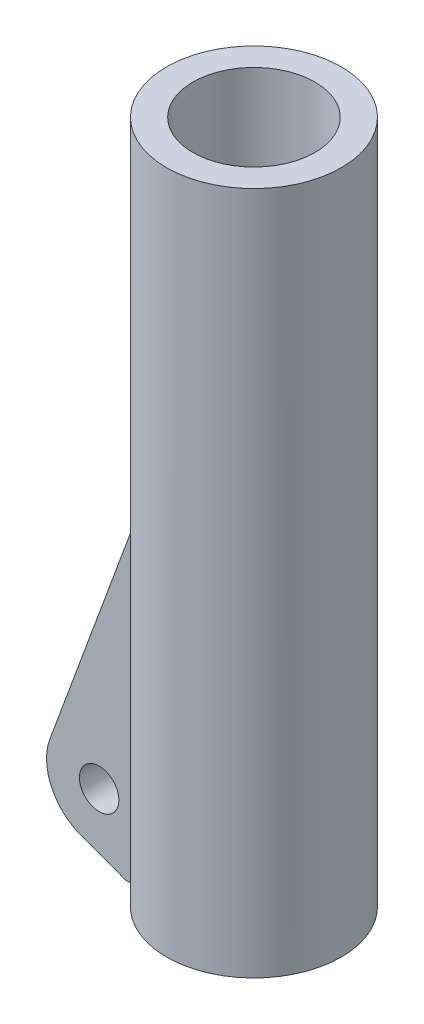
SolidWorks part; units mm, degrees
material "Choose your Material"
ref_plane "Front Plane" through (0, 0, 0) normal (0, 0, 1) x (1, 0, 0)
ref_plane "Top Plane" through (0, 0, 0) normal (0, 1, 0) x (1, 0, 0)
ref_plane "Right Plane" through (0, 0, 0) normal (1, 0, 0) x (0, 0, -1)
sketch "Sketch1" plane through (0, 0, 0) normal (0, 1, 0) x (1, 0, 0)
  circle A0 centre (0, 0) radius 29.464
  circle A1 centre (0, 0) radius 42.164
  dimension "D1" = 58.928
  dimension "D2" = 12.7
extrude "Boss-Extrude1" add sketch "Sketch1" along normal mid plane 329.946
sketch "Sketch2" plane through (0, 0, 0) normal (0, 0, 1) x (1, 0, 0)
  line L0 (-42.164, 164.973) -> (-42.164, -164.973) construction
  line L1 (-63.6469, -157.0562) -> (-42.164, -164.973)
  line L2 (-78.6972, -124.4401) -> (-29.464, 9.158)
  line L3 (-42.164, -164.973) -> (42.164, -164.973) construction
  line L4 (-42.164, -164.973) -> (-29.464, -164.973)
  line L5 (-29.464, -164.973) -> (-29.464, 9.158)
  arc A0 (-78.6972, -124.4401) -> (-63.6469, -157.0562) centre (-54.864, -133.223) ccw
  circle A1 centre (-54.864, -133.223) radius 9.525
  dimension "D2" = 50.8
  dimension "D4" = 19.05
  dimension "D1" = 12.7
  dimension "D3" = 31.75
  dimension "D5" = 12.7
extrude "Boss-Extrude2" add sketch "Sketch2" along normal mid plane 39.6875
equation "\"diameter\"= 18.75"
equation "\"OleoDia\"=2.32"
equation "\"D1@Sketch1\"=\"OleoDia\""
equation "\"D1@Boss-Extrude1\"=\"diameter\"/1.25"
equation "\"D1@Boss-Extrude2\"=\"diameter\"/12"
